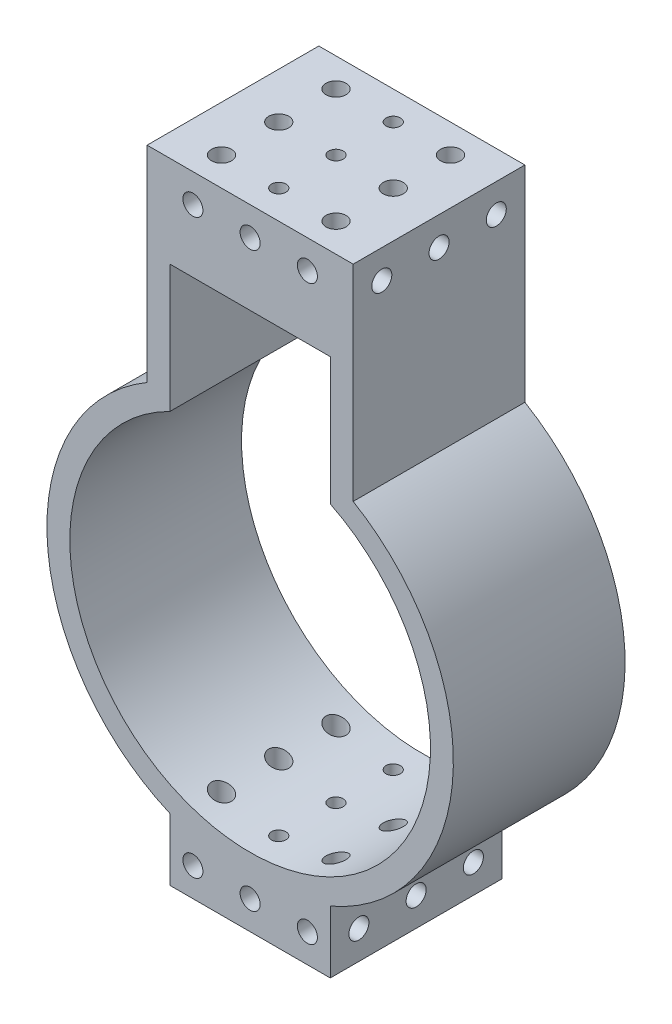
SolidWorks part; units mm, degrees
ref_plane "Plan de face" through (0, 0, 0) normal (0, 0, 1) x (1, 0, 0)
ref_plane "Plan de dessus" through (0, 0, 0) normal (0, 1, 0) x (1, 0, 0)
ref_plane "Plan de droite" through (0, 0, 0) normal (1, 0, 0) x (0, 0, -1)
sketch "Esquisse1" plane through (0, 0, 0) normal (0, 0, 1) x (1, 0, 0)
  line L0 (0, 31.5) -> (21.4959, 31.5) construction
  line L1 (21.4959, 50.5) -> (-25.7051, 50.5) construction
  line L2 (-14, 50.5) -> (-14, 18.3699) construction
  line L3 (14, 18.3699) -> (14, 50.5) construction
  line L4 (-14, 28.2179) -> (-14, 50.5)
  line L5 (-14, 50.5) -> (14, 50.5)
  line L6 (14, 50.5) -> (14, 28.2179)
  line L7 (18, 54.5) -> (18, 30.5982)
  line L8 (-18, 30.5982) -> (-18, 54.5)
  line L9 (-18, 54.5) -> (18, 54.5)
  line L10 (14, -32.6228) -> (14, -43.5)
  line L11 (14, -43.5) -> (-14, -43.5)
  line L12 (-14, -43.5) -> (-14, -32.6228)
  circle A0 centre (0, 0) radius 31.5 construction
  arc A1 (-14, 28.2179) -> (14, 28.2179) centre (0, 0) ccw
  arc A2 (-18, 30.5982) -> (18, 30.5982) centre (0, 0) ccw construction
  arc A3 (18, 30.5982) -> (14, -32.6228) centre (0, 0) cw
  arc A4 (-14, -32.6228) -> (-18, 30.5982) centre (0, 0) cw
  dimension "D1" = 63
  dimension "D5" = 4
  dimension "D2" = 19
  dimension "D3" = 14
  dimension "D4" = 14
  dimension "D6" = 98
extrude "Boss.-Extru.1" add sketch "Esquisse1" along normal blind 30
sketch "Esquisse3" plane through (0, 54.5, 0) normal (0, 1, 0) x (1, 0, 0)
  line L1 (-18, -30) -> (18, -30)
  line L2 (-18, -30) -> (-18, 0)
  line L3 (-18, 0) -> (18, 0)
  line L4 (18, -30) -> (18, 0)
extrude "Boss.-Extru.2" add sketch "Esquisse3" along normal blind 12
sketch "Esquisse2" plane through (0, 66.5, 0) normal (0, 1, 0) x (1, 0, 0)
  line L0 (0, 0) -> (0, -30) construction
  line L3 (-18, 0) -> (18, 0) construction
  line L4 (18, -30) -> (-18, -30) construction
  line L6 (-10, -30) -> (-10, 0) construction
  circle A0 centre (0, -5) radius 1.25
  circle A1 centre (0, -15) radius 1.25
  circle A2 centre (-10, -5) radius 1.75
  circle A3 centre (10, -5) radius 1.75
  circle A4 centre (10, -15) radius 1.75
  circle A5 centre (10, -25) radius 1.75
  circle A6 centre (-10, -15) radius 1.75
  circle A7 centre (-10, -25) radius 1.75
  circle A8 centre (0, -25) radius 1.25
  dimension "D1" = 5
  dimension "D3" = 3
  dimension "D4" = 10
  dimension "D5" = 3.5
  dimension "D2" = 2.5
  dimension "D6" = 5
  dimension "D7" = 2
  dimension "D8" = 3
extrude "Enlèv. mat.-Extru.1" cut sketch "Esquisse2" against normal through all
sketch "Esquisse4" plane through (18, 0, 0) normal (1, 0, 0) x (0, 0, -1)
  line L0 (-30, 61.5) -> (0, 61.5) construction
  line L1 (-30, 30.5982) -> (-30, 66.5) construction
  line L2 (0, 30.5982) -> (0, 66.5) construction
  line L3 (0, 66.5) -> (-30, 66.5) construction
  circle A0 centre (-25, 61.5) radius 1.75
  circle A1 centre (-15, 61.5) radius 1.75
  circle A2 centre (-5, 61.5) radius 1.75
  circle A3 centre (-5, -38.5) radius 1.75
  circle A4 centre (-15, -38.5) radius 1.75
  circle A5 centre (-25, -38.5) radius 1.75
  dimension "D2" = 3.5
  dimension "D1" = 5
  dimension "D3" = 5
  dimension "D6" = 100
  dimension "D4" = 3
  dimension "D5" = 2
extrude "Enlèv. mat.-Extru.2" cut sketch "Esquisse4" against normal through all
sketch "Esquisse5" plane through (0, 0, 30) normal (0, 0, 1) x (1, 0, 0)
  line L0 (18, 61.5) -> (-18, 61.5) construction
  line L1 (18, 30.5982) -> (18, 66.5) construction
  line L2 (-18, 66.5) -> (-18, 30.5982) construction
  line L3 (-18, 66.5) -> (18, 66.5) construction
  line L4 (0, 66.5) -> (0, -43.5) construction
  line L5 (-14, -43.5) -> (14, -43.5) construction
  circle A0 centre (10, 61.5) radius 1.75
  circle A1 centre (0, 61.5) radius 1.75
  circle A2 centre (-10, 61.5) radius 1.75
  circle A3 centre (0, -38.5) radius 1.75
  circle A4 centre (-10, -38.5) radius 1.75
  circle A5 centre (10, -38.5) radius 1.75
  dimension "D2" = 3.5
  dimension "D1" = 5
  dimension "D3" = 10
  dimension "D4" = 3
  dimension "D5" = 2
extrude "Enlèv. mat.-Extru.3" cut sketch "Esquisse5" against normal through all
